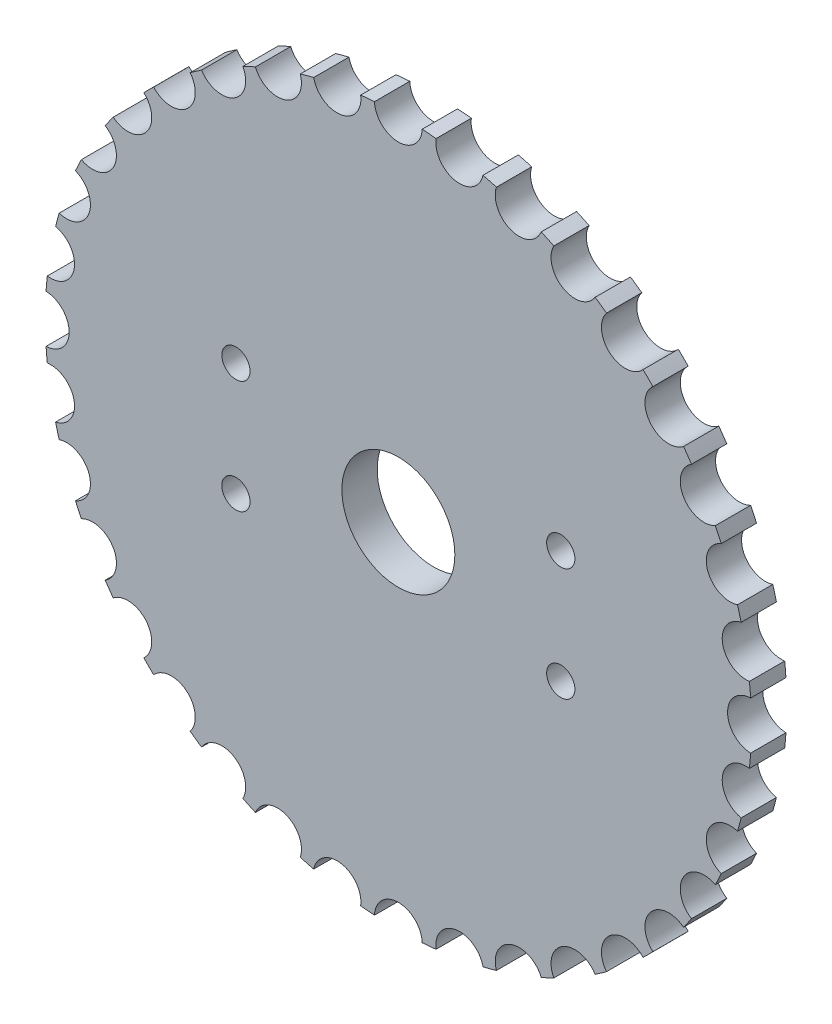
SolidWorks part; units mm, degrees
material "아크릴(내충격성)"
ref_plane "정면" through (0, 0, 0) normal (0, 0, 1) x (1, 0, 0)
ref_plane "윗면" through (0, 0, 0) normal (0, 1, 0) x (1, 0, 0)
ref_plane "우측면" through (0, 0, 0) normal (1, 0, 0) x (0, 0, -1)
sketch "스케치1" plane through (0, 0, 0) normal (0, 0, 1) x (1, 0, 0)
  circle A0 centre (0, 0) radius 50
  dimension "D1" = 100
extrude "보스-돌출1" add sketch "스케치1" along normal blind 5
sketch "스케치2" plane through (0, 0, 5) normal (0, 0, 1) x (1, 0, 0)
  line L0 (0, 0) -> (0, 53.4651) construction
  line L1 (0, 0) -> (9.1386, 52.0133) construction
  line L2 (0, 0) -> (-9.7027, 52.5525) construction
  circle A0 centre (4.373, 49.8084) radius 3.38
  circle A2 centre (0, 0) radius 50 construction
  circle A6 centre (11.6601, 43.4631) radius 3.38
  circle A7 centre (17.7347, 35.9488) radius 3.38
  circle A8 centre (22.4122, 27.4938) radius 3.38
  circle A9 centre (25.5503, 18.3551) radius 3.38
  circle A10 centre (27.0539, 8.8102) radius 3.38
  circle A11 centre (26.8772, -0.8507) radius 3.38
  circle A12 centre (25.0256, -10.3342) radius 3.38
  circle A13 centre (21.5553, -19.3521) radius 3.38
  circle A14 centre (16.5718, -27.6304) radius 3.38
  circle A15 centre (10.2265, -34.9175) radius 3.38
  circle A16 centre (2.7122, -40.9921) radius 3.38
  circle A17 centre (-5.7428, -45.6695) radius 3.38
  circle A18 centre (-14.8815, -48.8077) radius 3.38
  circle A19 centre (-24.4264, -50.3113) radius 3.38
  circle A20 centre (-34.0873, -50.1346) radius 3.38
  circle A21 centre (-43.5708, -48.283) radius 3.38
  circle A22 centre (-52.5887, -44.8127) radius 3.38
  circle A23 centre (-60.867, -39.8292) radius 3.38
  circle A24 centre (-68.1541, -33.4839) radius 3.38
  circle A25 centre (-74.2287, -25.9696) radius 3.38
  circle A26 centre (-78.9061, -17.5146) radius 3.38
  circle A27 centre (-82.0443, -8.3759) radius 3.38
  circle A28 centre (-83.5479, 1.169) radius 3.38
  circle A29 centre (-83.3712, 10.83) radius 3.38
  circle A30 centre (-81.5196, 20.3134) radius 3.38
  circle A31 centre (-78.0493, 29.3313) radius 3.38
  circle A32 centre (-73.0658, 37.6096) radius 3.38
  circle A33 centre (-66.7205, 44.8967) radius 3.38
  circle A34 centre (-59.2062, 50.9713) radius 3.38
  circle A35 centre (-50.7512, 55.6487) radius 3.38
  circle A36 centre (-41.6124, 58.7869) radius 3.38
  circle A37 centre (-32.0676, 60.2905) radius 3.38
  circle A38 centre (-22.4066, 60.1138) radius 3.38
  circle A39 centre (-12.9231, 58.2622) radius 3.38
  circle A40 centre (-3.9053, 54.7919) radius 3.38
  dimension "D1" = 106.9058
  dimension "D2" = 36
sketch "스케치4" plane through (0, 0, 5) normal (0, 0, 1) x (1, 0, 0)
  circle A0 centre (0, 0) radius 8
  dimension "D1" = 16
extrude "컷-돌출3" cut sketch "스케치4" against normal blind 10
sketch "스케치5" plane through (0, 0, 5) normal (0, 0, 1) x (1, 0, 0)
  line L0 (-52.1074, 0) -> (52.2141, 0) construction
  line L1 (-52.1074, -15) -> (52.2141, -15)
  line L2 (-52.1074, 15) -> (52.2141, 15)
  line L3 (0, 53.1222) -> (0, -55.2945) construction
  line L4 (-30, 53.1222) -> (-30, -55.2945)
  line L5 (30, 53.1222) -> (30, -55.2945)
  circle A0 centre (-23, 8) radius 2
  circle A1 centre (23, 8) radius 2
  circle A2 centre (23, -8) radius 2
  circle A3 centre (-23, -8) radius 2
  dimension "D5" = 4
  dimension "D7" = 7
  dimension "D6" = 7
  dimension "D1" = 15
  dimension "D2" = 15
  dimension "D3" = 30
  dimension "D4" = 30
extrude "컷-돌출4" cut sketch "스케치5" against normal blind 10 contours A3 | A0 | A1 | A2
sketch "스케치6" plane through (0, 0, 5) normal (0, 0, 1) x (1, 0, 0)
  line L0 (0, 0) -> (0, 53.4651) construction
  circle A0 centre (0, 50) radius 3.38
  circle A1 centre (0, 0) radius 50 construction
  circle A2 centre (8.6824, 49.2404) radius 3.38
  circle A3 centre (17.101, 46.9846) radius 3.38
  circle A4 centre (25, 43.3013) radius 3.38
  circle A5 centre (32.1394, 38.3022) radius 3.38
  circle A6 centre (38.3022, 32.1394) radius 3.38
  circle A7 centre (43.3013, 25) radius 3.38
  circle A8 centre (46.9846, 17.101) radius 3.38
  circle A9 centre (49.2404, 8.6824) radius 3.38
  circle A10 centre (50, 0) radius 3.38
  circle A11 centre (49.2404, -8.6824) radius 3.38
  circle A12 centre (46.9846, -17.101) radius 3.38
  circle A13 centre (43.3013, -25) radius 3.38
  circle A14 centre (38.3022, -32.1394) radius 3.38
  circle A15 centre (32.1394, -38.3022) radius 3.38
  circle A16 centre (25, -43.3013) radius 3.38
  circle A17 centre (17.101, -46.9846) radius 3.38
  circle A18 centre (8.6824, -49.2404) radius 3.38
  circle A19 centre (0, -50) radius 3.38
  circle A20 centre (-8.6824, -49.2404) radius 3.38
  circle A21 centre (-17.101, -46.9846) radius 3.38
  circle A22 centre (-25, -43.3013) radius 3.38
  circle A23 centre (-32.1394, -38.3022) radius 3.38
  circle A24 centre (-38.3022, -32.1394) radius 3.38
  circle A25 centre (-43.3013, -25) radius 3.38
  circle A26 centre (-46.9846, -17.101) radius 3.38
  circle A27 centre (-49.2404, -8.6824) radius 3.38
  circle A28 centre (-50, 0) radius 3.38
  circle A29 centre (-49.2404, 8.6824) radius 3.38
  circle A30 centre (-46.9846, 17.101) radius 3.38
  circle A31 centre (-43.3013, 25) radius 3.38
  circle A32 centre (-38.3022, 32.1394) radius 3.38
  circle A33 centre (-32.1394, 38.3022) radius 3.38
  circle A34 centre (-25, 43.3013) radius 3.38
  circle A35 centre (-17.101, 46.9846) radius 3.38
  circle A36 centre (-8.6824, 49.2404) radius 3.38
  point P79 (0, 0)
  dimension "D1" = 36
extrude "컷-돌출5" cut sketch "스케치6" against normal through all
